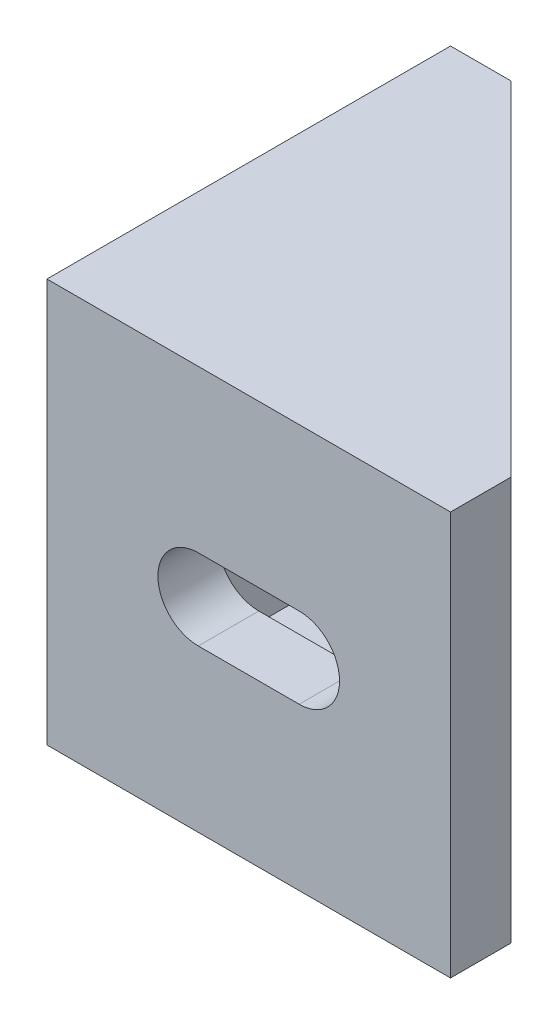
SolidWorks part; units mm, degrees
ref_plane "前视基准面" through (0, 0, 0) normal (0, 0, 1) x (1, 0, 0)
ref_plane "上视基准面" through (0, 0, 0) normal (0, 1, 0) x (1, 0, 0)
ref_plane "右视基准面" through (0, 0, 0) normal (1, 0, 0) x (0, 0, -1)
sketch "草图1" plane through (0, 0, 0) normal (0, 1, 0) x (1, 0, 0)
  line L0 (0, 0) -> (20, 0)
  line L1 (0, 0) -> (0, 20)
  dimension "D1" = 20
  dimension "D2" = 20
extrude "拉伸-薄壁2" add sketch "草图1" along normal blind 20 thin contours L1 L0 thin type one direction wall 3
sketch "草图2" plane through (0, 20, 0) normal (0, 1, 0) x (1, 0, 0)
  line L0 (3, 20) -> (20, 3)
  line L7 (3, 3) -> (3, 20)
  line L8 (3, 20) -> (0, 20)
  line L9 (0, 20) -> (0, 0)
  line L10 (0, 0) -> (20, 0)
  line L11 (20, 0) -> (20, 3)
  line L12 (20, 3) -> (3, 3)
  line L14 (3, 20) -> (0, 20)
  line L15 (0, 20) -> (0, 0)
  line L16 (0, 0) -> (20, 0)
  line L17 (20, 0) -> (20, 3)
  dimension "D1" = 0
extrude "凸台-拉伸1" add sketch "草图2" against normal blind 3
sketch "草图3" plane through (0, 0, 0) normal (0, -1, 0) x (1, 0, 0)
  line L0 (20, -3) -> (3, -20)
  line L1 (3, -20) -> (3, -3)
  line L2 (3, -3) -> (20, -3)
ref_plane "基准面1" through (3, 0, -3) normal (0, 0, -1) x (-1, 0, 0)
extrude "凸台-拉伸2" add sketch "草图3" against normal blind 3 contours L0 L1 L2
sketch "草图5" plane through (0, 0, -3) normal (0, 0, -1) x (-1, 0, 0)
  line L0 (-7.5, 10) -> (-12.5, 10) construction
  line L1 (-7.5, 8) -> (-12.5, 8)
  line L2 (-7.5, 12) -> (-12.5, 12)
  line L3 (-20, 17) -> (-20, 3) construction
  arc A0 (-7.5, 8) -> (-7.5, 12) centre (-7.5, 10) ccw
  arc A1 (-12.5, 12) -> (-12.5, 8) centre (-12.5, 10) ccw
  point P2 (-10, 10)
  dimension "D3" = 2
  dimension "D1" = 5
  dimension "D2" = 10
  dimension "D4" = 10
extrude "切除-拉伸1" cut sketch "草图5" against normal through all contours A1 L1 A0 L2
sketch "草图6" plane through (3, 0, 0) normal (1, 0, 0) x (0, 0, -1)
  line L0 (7.5, 10) -> (12.5, 10) construction
  line L1 (7.5, 12) -> (12.5, 12)
  line L2 (7.5, 8) -> (12.5, 8)
  line L3 (3, 0) -> (20, 0) construction
  line L4 (20, 17) -> (20, 3) construction
  arc A0 (7.5, 12) -> (7.5, 8) centre (7.5, 10) ccw
  arc A1 (12.5, 8) -> (12.5, 12) centre (12.5, 10) ccw
  point P2 (10, 10)
  dimension "D4" = 2
  dimension "D1" = 5
  dimension "D2" = 10
  dimension "D3" = 10
extrude "切除-拉伸2" cut sketch "草图6" against normal through all
